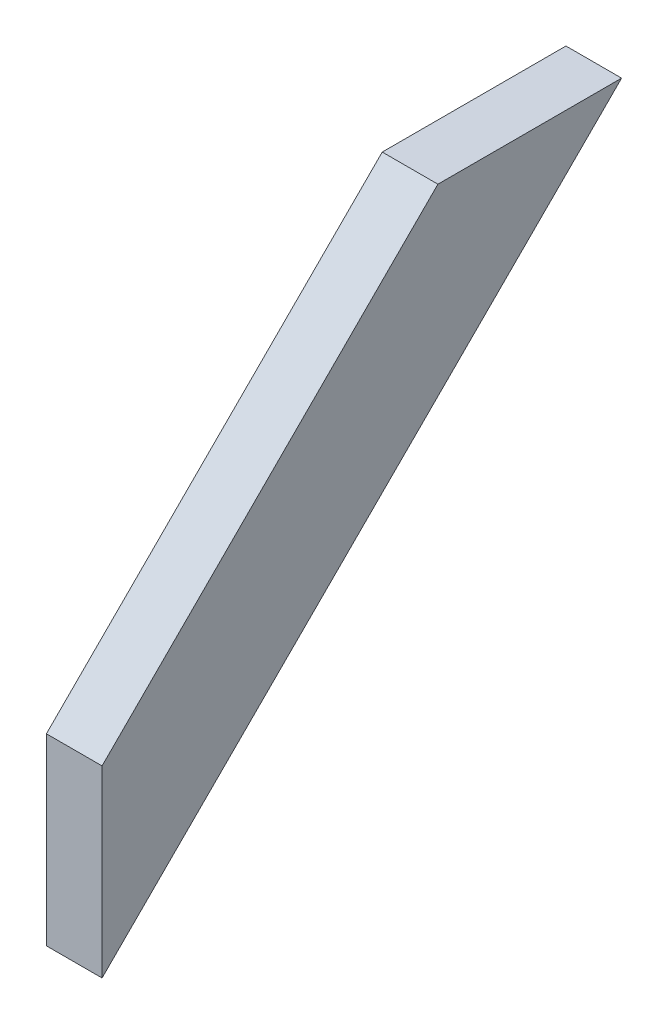
SolidWorks part; units mm, degrees
material "Pine"
ref_plane "Front Plane" through (0, 0, 0) normal (0, 0, 1) x (1, 0, 0)
ref_plane "Top Plane" through (0, 0, 0) normal (0, 1, 0) x (1, 0, 0)
ref_plane "Right Plane" through (0, 0, 0) normal (1, 0, 0) x (0, 0, -1)
sketch "Sketch1" plane through (0, 0, 0) normal (1, 0, 0) x (0, 0, -1)
  line L0 (0, 0) -> (0, 125.7236)
  line L1 (0, 125.7236) -> (229.8764, 355.6)
  line L2 (229.8764, 355.6) -> (355.6, 355.6)
  line L3 (355.6, 355.6) -> (0, 0)
  dimension "D1" = 45
  dimension "D2" = 355.6
  dimension "D3" = 88.9
extrude "Boss-Extrude1" add sketch "Sketch1" along normal blind 38.1
